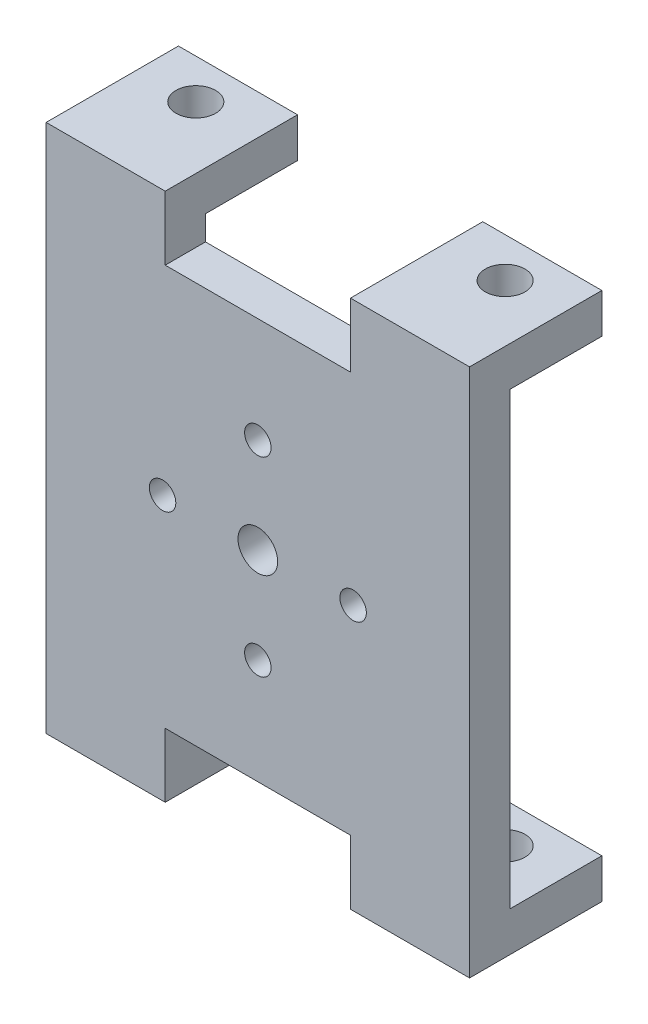
SolidWorks part; units mm, degrees
ref_plane "Front Plane" through (0, 0, 0) normal (0, 0, 1) x (1, 0, 0)
ref_plane "Top Plane" through (0, 0, 0) normal (0, 1, 0) x (1, 0, 0)
ref_plane "Right Plane" through (0, 0, 0) normal (1, 0, 0) x (0, 0, -1)
sketch "Sketch1" plane through (0, 0, 0) normal (0, 0, 1) x (1, 0, 0)
  line L1 (16, -20) -> (-16, -20)
  line L2 (16, -20) -> (16, 20)
  line L3 (16, 20) -> (-16, 20)
  line L4 (-16, -20) -> (-16, 20)
  line L5 (16, -20) -> (-16, 20) construction
  line L6 (16, 20) -> (-16, -20) construction
  point P0 (0, 0)
  dimension "D1" = 32
  dimension "D2" = 40
extrude "Boss-Extrude1" add sketch "Sketch1" along normal blind 2 and the other way blind 1.0436
sketch "Sketch2" plane through (0, 0, 2) normal (0, 0, 1) x (1, 0, 0)
  line L0 (0, 0) -> (16, 0) construction
  line L1 (16, -20) -> (16, 20) construction
  line L2 (0, -13.1561) -> (5, -13.1561)
  line L3 (7, -15.1561) -> (7, -21)
  line L4 (-16, -20) -> (16, -20) construction
  line L5 (7, -21) -> (16, -21)
  line L6 (16, -21) -> (16, -13)
  line L7 (0, 0) -> (0, -20.9059) construction
  line L8 (16, -13) -> (14, -13)
  line L9 (16, 13) -> (14, 13)
  line L10 (16, 21) -> (16, 13)
  line L11 (7, 21) -> (16, 21)
  line L12 (7, 15.1561) -> (7, 21)
  line L13 (0, 13.1561) -> (5, 13.1561)
  line L14 (0, 13.1561) -> (-5, 13.1561)
  line L15 (-7, 15.1561) -> (-7, 21)
  line L16 (-7, 21) -> (-16, 21)
  line L17 (-16, 21) -> (-16, 13)
  line L18 (-16, 13) -> (-14, 13)
  line L19 (-16, -13) -> (-14, -13)
  line L20 (-16, -21) -> (-16, -13)
  line L21 (-7, -21) -> (-16, -21)
  line L22 (-7, -15.1561) -> (-7, -21)
  line L23 (-5, -13.1561) -> (0, -13.1561)
  line L24 (-13.1561, 0) -> (-13.1561, -5) [skipped]
  line L25 (-21, -7) -> (-21, -16) [skipped]
  line L26 (-21, -16) -> (-13, -16) [skipped]
  line L27 (-15.1561, -7) -> (-21, -7) [skipped]
  line L28 (-13, -16) -> (-13, -14) [skipped]
  line L29 (13.1561, 0) -> (13.1561, 5) [skipped]
  line L30 (21, 7) -> (21, 16) [skipped]
  line L31 (15.1561, 7) -> (21, 7) [skipped]
  line L32 (21, 16) -> (13, 16) [skipped]
  line L33 (13, 16) -> (13, 14) [skipped]
  line L35 (23.2935, -20.5348) -> (-23.2935, -20.5348)
  line L36 (23.2935, -20.5348) -> (23.2935, 20.5348)
  line L37 (23.2935, 20.5348) -> (-23.2935, 20.5348)
  line L38 (-23.2935, -20.5348) -> (-23.2935, 20.5348)
  line L39 (23.2935, -20.5348) -> (-23.2935, 20.5348) construction
  line L40 (23.2935, 20.5348) -> (-23.2935, -20.5348) construction
  arc A0 (5, 13.1561) -> (7, 15.1561) centre (5, 15.1561) ccw
  arc A1 (5, -13.1561) -> (7, -15.1561) centre (5, -15.1561) cw
  arc A2 (-5, 13.1561) -> (-7, 15.1561) centre (-5, 15.1561) cw
  arc A3 (-5, -13.1561) -> (-7, -15.1561) centre (-5, -15.1561) ccw
  arc A4 (-13.1561, -5) -> (-15.1561, -7) centre (-15.1561, -5) cw [skipped]
  arc A5 (13.1561, 5) -> (15.1561, 7) centre (15.1561, 5) cw [skipped]
  arc A6 (-14, 13) -> (-14, -13) centre (-21.4833, 0) cw
  arc A7 (14, 13) -> (14, -13) centre (21.4833, 0) ccw
  point P44 (0, 0)
  dimension "D2" = 2
  dimension "D6" = 15
  dimension "D7" = 15
  dimension "D1" = 6.8439
  dimension "D3" = 8
  dimension "D4" = 2
  dimension "D8" = 9
  dimension "D5" = 4
sketch "Sketch5" plane through (0, 0, 2) normal (0, 0, 1) x (1, 0, 0)
  circle A0 centre (0, 0) radius 1.5
  circle A1 centre (0, 7.2) radius 1
  circle A2 centre (7.2, 0) radius 1
  circle A3 centre (0, -7.2) radius 1
  circle A4 centre (-7.2, 0) radius 1
  point P14 (0, 0)
  dimension "D1" = 3
  dimension "D2" = 2
  dimension "D3" = 7.2
  dimension "D4" = 4
extrude "Cut-Extrude3" cut sketch "Sketch5" against normal through all both and the other way through all
sketch "草图4" plane through (0, 0, 2) normal (0, 0, 1) x (1, 0, 0)
  line L0 (7, 20) -> (7, 15.1561)
  line L3 (7, 15.1561) -> (-7, 15.1561)
  line L4 (-7, 15.1561) -> (-7, 20)
  line L15 (7, -20) -> (7, -15.1561)
  line L18 (7, -15.1561) -> (-7, -15.1561)
  line L19 (-7, -15.1561) -> (-7, -20)
  line L25 (-16, 20) -> (-16, -20)
  line L26 (-16, -20) -> (16, -20)
  line L27 (16, -20) -> (16, 20)
  line L28 (16, 20) -> (-16, 20)
  line L29 (-16, 20) -> (-16, -20)
  line L30 (-16, -20) -> (16, -20)
  line L31 (16, -20) -> (16, 20)
  line L32 (16, 20) -> (-16, 20)
  line M13 (-16, -20) -> (16, -20)
  line M15 (16, 20) -> (-16, 20)
  dimension "D3" = 0
extrude "切除-拉伸3" cut sketch "草图4" against normal through all contours L4 L3 L0 M15 | L18 L19 L15 M13
sketch "草图5" plane through (0, 0, 2) normal (0, 0, 1) x (1, 0, 0)
  line L0 (16, 21) -> (16, 13) construction
  line L1 (7, 20) -> (16, 20)
  line L2 (7, 20) -> (7, 17)
  line L3 (7, 17) -> (16, 17)
  line L4 (16, 20) -> (16, 17)
  line L5 (-7, 15.1561) -> (-7, 21) construction
  line L6 (-16, 20) -> (-7, 20)
  line L7 (-16, 20) -> (-16, 17)
  line L8 (-16, 17) -> (-7, 17)
  line L9 (-7, 20) -> (-7, 17)
  line L10 (-7, -15.1561) -> (-7, -21) construction
  line L11 (-16, -20) -> (-7, -20)
  line L12 (-16, -20) -> (-16, -17)
  line L13 (-16, -17) -> (-7, -17)
  line L14 (-7, -20) -> (-7, -17)
  line L15 (7, -15.1561) -> (7, -21) construction
  line L16 (16, -20) -> (7, -20)
  line L17 (16, -20) -> (16, -17)
  line L18 (16, -17) -> (7, -17)
  line L19 (7, -20) -> (7, -17)
extrude "凸台-拉伸3" add sketch "草图5" against normal blind 10
sketch "草图6" plane through (0, -20, 0) normal (0, -1, 0) x (1, 0, 0)
  line L0 (-16, -8) -> (-7, -8) construction
  line L1 (-7, -8) -> (-7, 2) construction
  line L2 (7, 2) -> (7, -8) construction
  line L3 (7, -8) -> (16, -8) construction
  line L4 (16, -8) -> (16, 2) construction
  line L5 (16, 2) -> (7, 2) construction
  line L6 (-7, 2) -> (-16, 2) construction
  line L7 (-16, 2) -> (-16, -8) construction
  line L8 (7, 2) -> (7, -8)
  line L9 (7, -8) -> (16, -8)
  line L10 (16, -8) -> (16, 2)
  line L11 (16, 2) -> (7, 2)
  line L12 (-7, -8) -> (-7, 2)
  line L13 (-7, 2) -> (-16, 2)
  line L14 (-16, 2) -> (-16, -8)
  line L15 (-16, -8) -> (-7, -8)
  circle A2 centre (11.6895, -5) radius 1.5
  circle A3 centre (-11.6895, -5) radius 1.5
  dimension "D1" = 23.379
  dimension "D2" = 4.6895
  dimension "D3" = 3
  dimension "D4" = 3
  dimension "D5" = 3
  dimension "D6" = 3
extrude "切除-拉伸5" cut sketch "草图6" against normal through all contours A3 | A2
